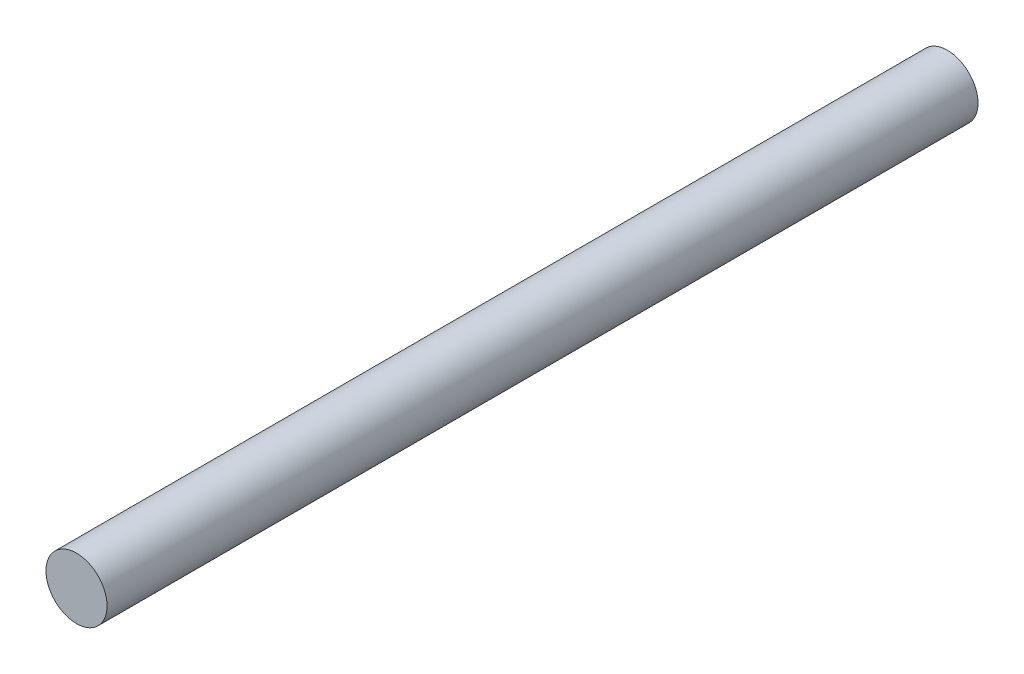
SolidWorks part; units mm, degrees
ref_plane "Front Plane" through (0, 0, 0) normal (0, 0, 1) x (1, 0, 0)
ref_plane "Top Plane" through (0, 0, 0) normal (0, 1, 0) x (1, 0, 0)
ref_plane "Right Plane" through (0, 0, 0) normal (1, 0, 0) x (0, 0, -1)
sketch "Sketch1" plane through (0, 0, 0) normal (0, 0, 1) x (1, 0, 0)
  circle A0 centre (0, 0) radius 3
  dimension "D1" = 6
extrude "Boss-Extrude1" add sketch "Sketch1" along normal blind 85.5
